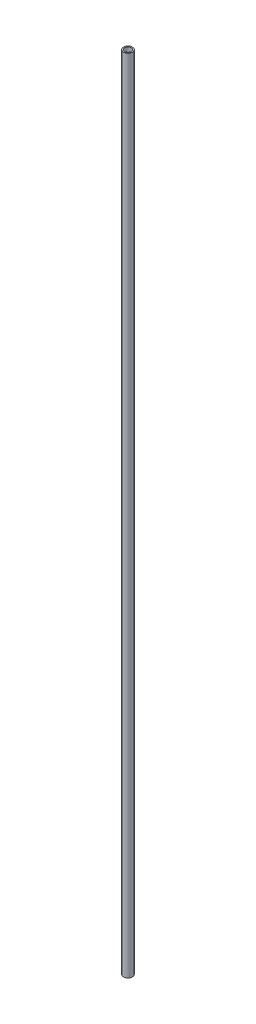
SolidWorks part; units mm, degrees
ref_plane "Front Plane" through (0, 0, 0) normal (0, 0, 1) x (1, 0, 0)
ref_plane "Top Plane" through (0, 0, 0) normal (0, 1, 0) x (1, 0, 0)
ref_plane "Right Plane" through (0, 0, 0) normal (1, 0, 0) x (0, 0, -1)
sketch "Sketch1" plane through (0, 0, 0) normal (0, 1, 0) x (1, 0, 0)
  circle A0 centre (0, 0) radius 13
  circle A1 centre (0, 0) radius 9.525
  dimension "D1" = 26
  dimension "D2" = 19.05
extrude "Boss-Extrude1" add sketch "Sketch1" along normal blind 2339.34
